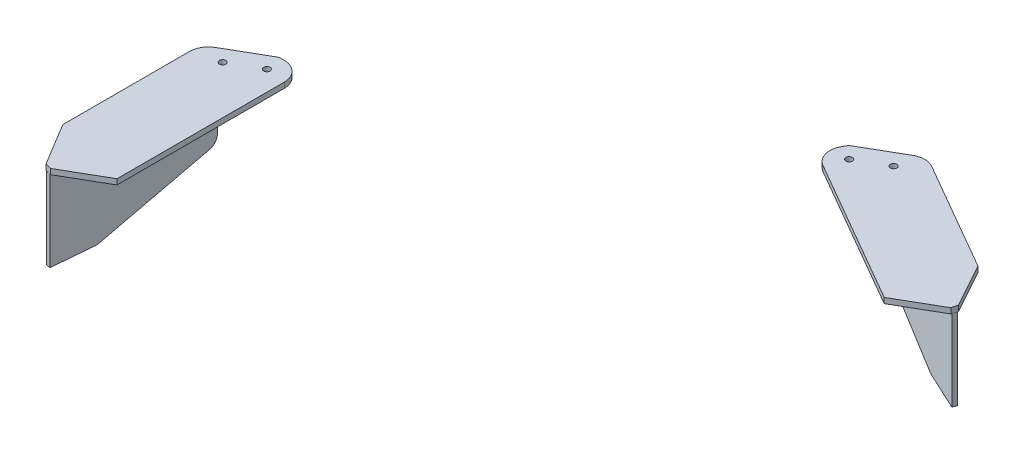
SolidWorks part; units mm, degrees
ref_plane "Front Plane" through (0, 0, 0) normal (0, 0, 1) x (1, 0, 0)
ref_plane "Top Plane" through (0, 0, 0) normal (0, 1, 0) x (1, 0, 0)
ref_plane "Right Plane" through (0, 0, 0) normal (1, 0, 0) x (0, 0, -1)
sketch "Sketch1" plane through (0, 0, 0) normal (0, 1, 0) x (1, 0, 0)
  line L0 (0, 194.44) -> (0, -194.44) construction
  line L1 (68.3013, 0) -> (-68.3013, 0) construction
  line L5 (68.3013, 194.44) -> (-68.3013, 194.44) construction
  line L7 (68.3013, 194.44) -> (68.3013, -194.44) construction
  line L9 (68.3013, -194.44) -> (-68.3013, -194.44) construction
  line L10 (-68.3013, -194.44) -> (-68.3013, 194.44) construction
  line L11 (23.9218, 194.44) -> (-50.8013, 151.2986)
  line L13 (23.9218, 194.44) -> (33.3013, 194.44)
  line L15 (68.3013, 159.44) -> (68.3013, -149.44)
  line L16 (68.3013, -149.44) -> (-9.641, -194.44)
  line L17 (-9.641, -194.44) -> (-20.8428, -191.4385)
  line L18 (-20.8428, -191.4385) -> (-68.3013, -112.84)
  line L19 (-68.3013, 120.9877) -> (-68.3013, -112.84)
  line L20 (31.55, 164.2031) -> (-20.4115, 134.2031) construction
  arc A0 (33.3013, 194.44) -> (68.3013, 159.44) centre (33.3013, 159.44) cw
  arc A1 (-50.8013, 151.2986) -> (-68.3013, 120.9877) centre (-33.3013, 120.9877) ccw
  circle A2 centre (31.55, 164.2031) radius 6
  circle A3 centre (-20.4115, 134.2031) radius 6
  point P6 (0, 194.44)
  point P8 (68.3013, 0)
  point P21 (-68.3013, 141.195)
  dimension "D12" = 31.55
  dimension "D14" = 60
  dimension "D9" = 35
  dimension "D10" = 35
  dimension "D13" = 12
  dimension "D1" = 136.6025
  dimension "D2" = 388.88
  dimension "D3" = 60
  dimension "D4" = 106.49
  dimension "D5" = 45
  dimension "D6" = 81.6
  dimension "D7" = 135
  dimension "D8" = 15
  dimension "D11" = 30
extrude "Boss-Extrude1" add sketch "Sketch1" along normal blind 10
sketch "Sketch2" plane through (0, 0, 0) normal (0, -1, 0) x (1, 0, 0)
  line L0 (68.3013, 0) -> (-68.3013, 0) construction
  line L1 (68.3013, 149.44) -> (68.3013, -159.44) construction
  line L2 (-68.3013, -120.9877) -> (-68.3013, 112.84) construction
  line L3 (-15.2419, 192.9392) -> (9.5975, -90.9762)
  line L4 (-20.8428, 191.4385) -> (-9.641, 194.44) construction
  dimension "D1" = 85
  dimension "D2" = 285
extrude "Extrude-Thin1" add sketch "Sketch2" along normal blind 150 separate body thin thin type mid plane wall 8
sketch "Sketch3" plane through (5.6104, 0, 0.4908) normal (0.9962, 0, 0.0872) x (0.0872, 0, -0.9962)
  line L0 (91.4665, -150) -> (-113.5335, -150)
  line L1 (-193.5335, -150) -> (91.4665, -150) construction
  line L4 (91.4665, -150) -> (91.4665, 0) construction
  line L5 (91.4665, -80) -> (-113.5335, -150)
  line L6 (91.4665, -150) -> (91.4665, -80)
extrude "Cut-Extrude1" cut sketch "Sketch3" against normal up to surface (8 mm away) up to face at (-6.807, -75, 50.6329)
fillet "Fillet1" radius 20 2 edges at (-8.2695, -150, 113.2437) (9.5975, -80, -90.9762)
ref_plane "Plane1" through (580.87, 0, 0) normal (1, 0, 0) x (0, 0, -1)
sketch "Sketch4" plane through (580.87, 0, 0) normal (1, 0, 0) x (0, 0, -1)
  line L0 (0, 0) -> (0, -155.7474) construction
ref_plane "Plane2" through (435.6525, 0, -251.5241) normal (-0.866, 0, 0.5) x (0, -1, 0)
mirror "Mirror2" about plane through (435.6525, 0, -251.5241) normal (-0.866, 0, 0.5) of bodies 101 103
sketch "Sketch5" plane through (0, 10, 0) normal (0, 1, 0) x (1, 0, 0)
  line L0 (1025.3475, 465.5791) -> (-44.572, -152.1392)
  line L1 (1003.1779, 505.7788) -> (1047.517, 425.3793) construction
  line L2 (-68.3013, -112.84) -> (-20.8428, -191.4385) construction
